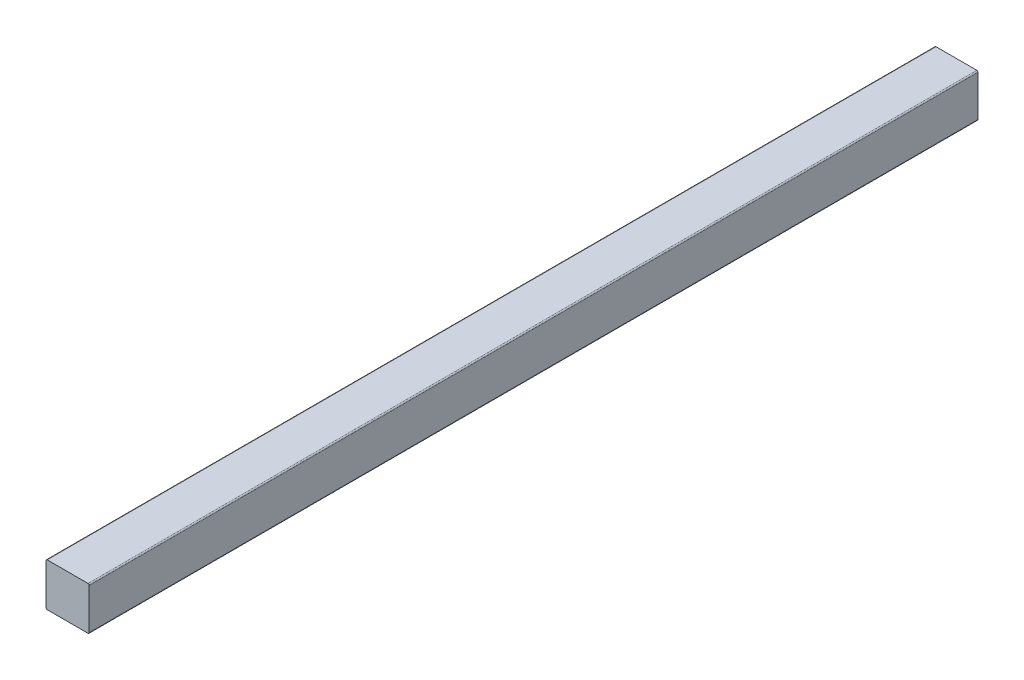
SolidWorks part; units mm, degrees
material "Pine"
ref_plane "Front Plane" through (0, 0, 0) normal (0, 0, 1) x (1, 0, 0)
ref_plane "Top Plane" through (0, 0, 0) normal (0, 1, 0) x (1, 0, 0)
ref_plane "Right Plane" through (0, 0, 0) normal (1, 0, 0) x (0, 0, -1)
sketch "Sketch1" plane through (0, 0, 0) normal (0, 0, 1) x (1, 0, 0)
  line L1 (-41.91, 44.45) -> (41.91, 44.45)
  line L2 (-44.45, 41.91) -> (-44.45, -41.91)
  line L3 (-41.91, -44.45) -> (41.91, -44.45)
  line L4 (44.45, 41.91) -> (44.45, -41.91)
  line L5 (-44.45, 44.45) -> (44.45, -44.45) construction
  line L6 (-44.45, -44.45) -> (44.45, 44.45) construction
  arc A0 (41.91, 44.45) -> (44.45, 41.91) centre (41.91, 41.91) cw
  arc A1 (41.91, -44.45) -> (44.45, -41.91) centre (41.91, -41.91) ccw
  arc A2 (-44.45, -41.91) -> (-41.91, -44.45) centre (-41.91, -41.91) ccw
  arc A3 (-41.91, 44.45) -> (-44.45, 41.91) centre (-41.91, 41.91) ccw
  point P0 (0, 0)
  dimension "D1" = 2.54
  dimension "D2" = 88.9
  dimension "D3" = 88.9
extrude "Boss-Extrude1" add sketch "Sketch1" along normal mid plane 1828.8
